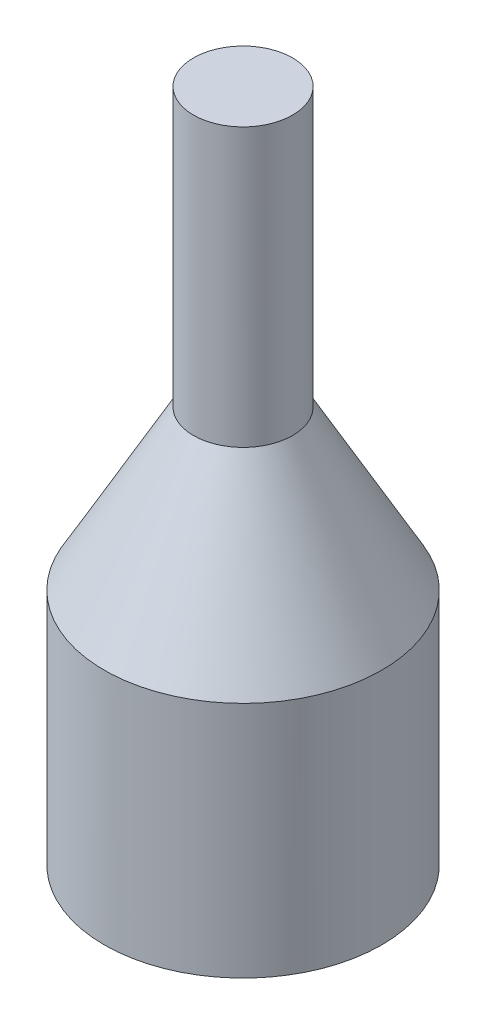
SolidWorks part; units mm, degrees
material "PET"
ref_plane "Front Plane" through (0, 0, 0) normal (0, 0, 1) x (1, 0, 0)
ref_plane "Top Plane" through (0, 0, 0) normal (0, 1, 0) x (1, 0, 0)
ref_plane "Right Plane" through (0, 0, 0) normal (1, 0, 0) x (0, 0, -1)
sketch "Sketch1" plane through (0, 0, 0) normal (0, 1, 0) x (1, 0, 0)
  circle A0 centre (0, 0) radius 7
  dimension "D1" = 14
extrude "Boss-Extrude1" add sketch "Sketch1" along normal blind 12
ref_plane "Plane2" through (0, 20, 0) normal (0, 1, 0) x (1, 0, 0)
sketch "Sketch3" plane through (0, 20, 0) normal (0, 1, 0) x (1, 0, 0)
  circle A0 centre (0, 0) radius 2.5
  dimension "D1" = 5
sketch "Sketch4" plane through (0, 12, 0) normal (0, 1, 0) x (1, 0, 0)
  circle A1 centre (0, 0) radius 7
  circle A2 centre (0, 0) radius 7
  dimension "D1" = 0
loft "Loft1" add profiles "Sketch3", "Sketch4"
sketch "Sketch5" plane through (0, 20, 0) normal (0, 1, 0) x (1, 0, 0)
  circle A1 centre (0, 0) radius 2.5
  circle A2 centre (0, 0) radius 2.5
  dimension "D1" = 0
extrude "Boss-Extrude2" add sketch "Sketch5" along normal blind 14
ref_plane "Plane3" through (0, 12, 0) normal (0, 1, 0) x (1, 0, 0)
sketch "Sketch6" plane through (0, 0, 0) normal (0, -1, 0) x (1, 0, 0)
  circle A0 centre (0, 0) radius 4
  dimension "D1" = 8
extrude "Cut-Extrude1" cut sketch "Sketch6" against normal blind 14
